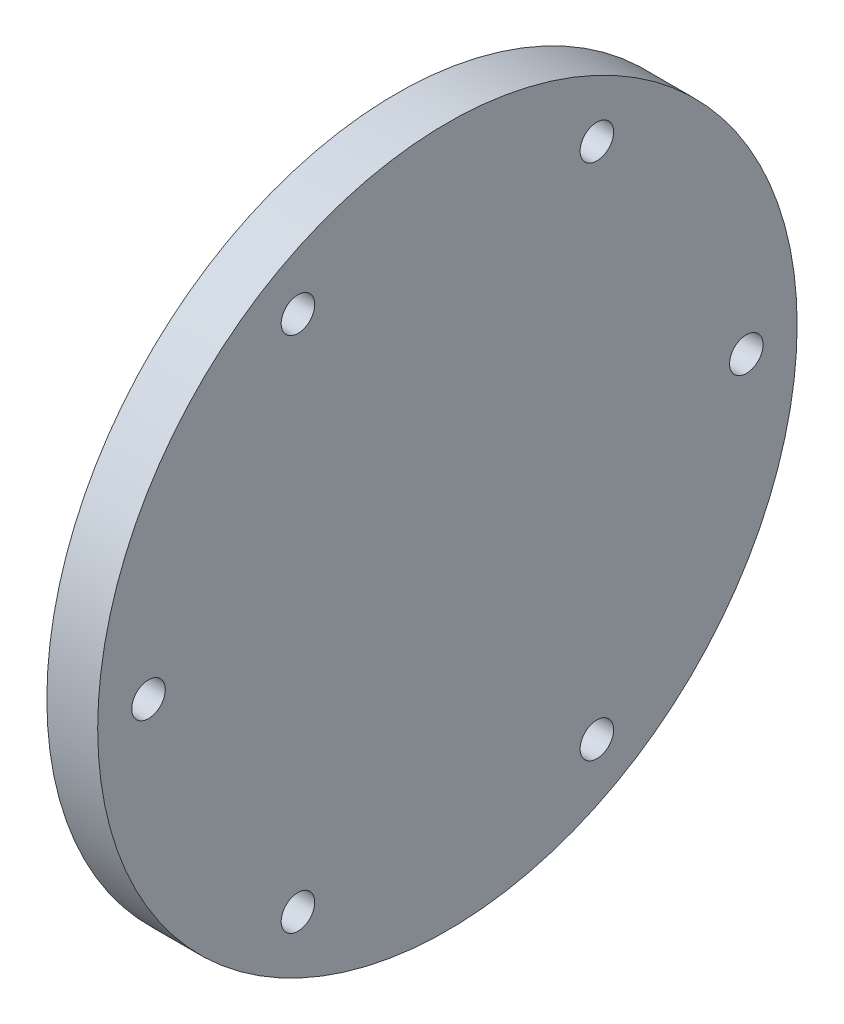
SolidWorks part; units mm, degrees
ref_plane "Front Plane" through (0, 0, 0) normal (0, 0, 1) x (1, 0, 0)
ref_plane "Top Plane" through (0, 0, 0) normal (0, 1, 0) x (1, 0, 0)
ref_plane "Right Plane" through (0, 0, 0) normal (1, 0, 0) x (0, 0, -1)
sketch "Axial profile (mm)" plane through (0, 0, 0) normal (0, 0, 1) x (1, 0, 0)
  line L0 (-110, 0) -> (75, 0) construction
  line L1 (163.7, 0) -> (168.7, 0)
  line L2 (168.7, 0) -> (168.7, 34.4)
  line L3 (168.7, 34.4) -> (163.7, 34.4)
  line L4 (163.7, 34.4) -> (163.7, 0)
revolve "Full revolution" add sketch "Axial profile (mm)" angle 360 about L0
sketch "Sketch2" plane through (0, 0, 0) normal (1, 0, 0) x (0, 0, -1)
  circle A0 centre (-29.4, 0) radius 1.65
  circle A1 centre (14.7, -25.4611) radius 1.65
  circle A2 centre (14.7, 25.4611) radius 1.65
  circle A3 centre (29.4, 0) radius 1.65
  circle A4 centre (-14.7, 25.4611) radius 1.65
  circle A5 centre (-14.7, -25.4611) radius 1.65
extrude "Axial holes" cut sketch "Sketch2" against normal through all and the other way through all
